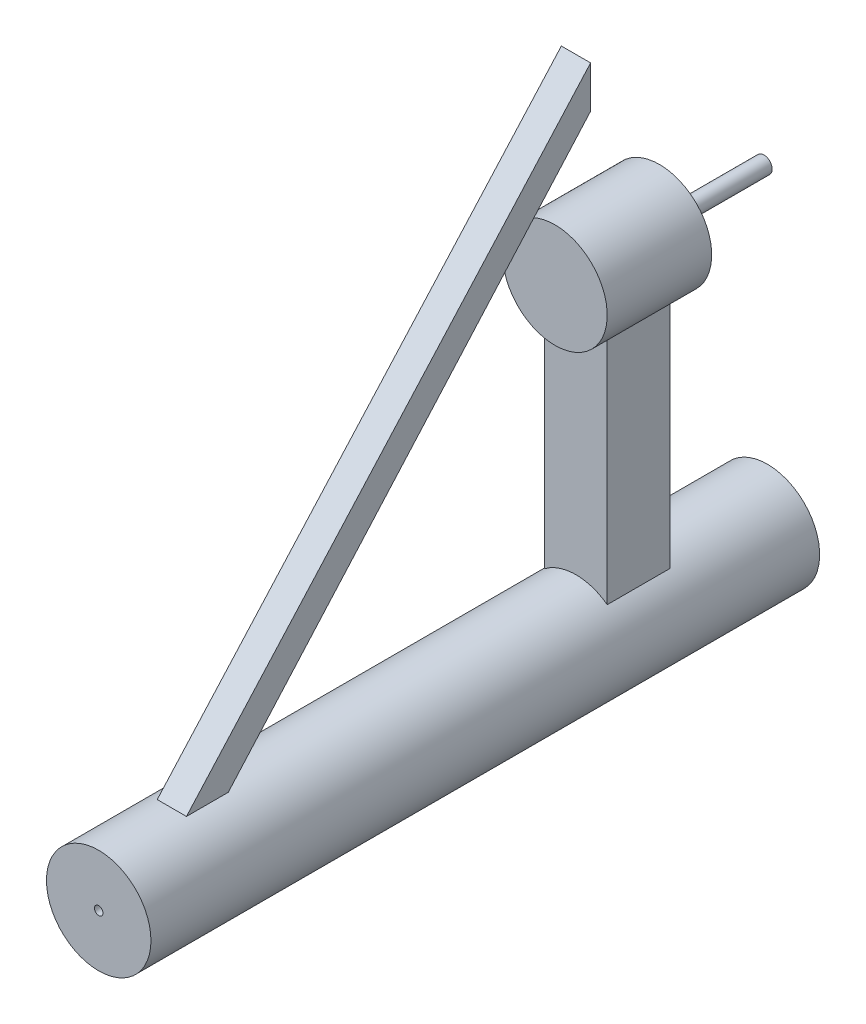
SolidWorks part; units mm, degrees
ref_plane "Alzado" through (0, 0, 0) normal (0, 0, 1) x (1, 0, 0)
ref_plane "Planta" through (0, 0, 0) normal (0, 1, 0) x (1, 0, 0)
ref_plane "Vista lateral" through (0, 0, 0) normal (1, 0, 0) x (0, 0, -1)
sketch "Croquis1" plane through (0, 0, 0) normal (0, 0, 1) x (1, 0, 0)
  circle A0 centre (0, 0) radius 25
  dimension "D1" = 50
extrude "Saliente-Extruir1" add sketch "Croquis1" along normal blind 270
sketch "Croquis2" plane through (0, 0, 0) normal (0, 1, 0) x (1, 0, 0)
  line L3 (-15.05, -11.6046) -> (14.95, -11.6046)
  line L4 (-15.05, -11.6046) -> (-15.05, -41.6046)
  line L5 (-15.05, -41.6046) -> (14.95, -41.6046)
  line L6 (14.95, -11.6046) -> (14.95, -41.6046)
  line L7 (-15.05, -11.6046) -> (14.95, -41.6046) construction
  line L8 (-15.05, -41.6046) -> (14.95, -11.6046) construction
  dimension "D1" = 30
  dimension "D3" = 30
extrude "Saliente-Extruir13" add sketch "Croquis2" along normal blind 150
ref_plane "Plano5" through (0, 0, 11.6046) normal (0, 0, -1) x (-1, 0, 0)
sketch "Croquis14" plane through (0, 0, 11.6046) normal (0, 0, -1) x (-1, 0, 0)
  line L0 (-14.95, 150) -> (15.05, 150) construction
  circle A0 centre (0.05, 150) radius 25
  dimension "D1" = 50
extrude "Saliente-Extruir14" add sketch "Croquis14" along normal blind 10 and the other way blind 40
ref_plane "Plano6" through (0, 0, 1.6046) normal (0, 0, -1) x (-1, 0, 0)
sketch "Croquis15" plane through (0, 0, 0) normal (1, 0, 0) x (0, 0, -1)
  line L0 (-41.6046, 240.6046) -> (-235, 25)
  line L2 (-41.6046, 25) -> (-270, 25) construction
  line L4 (-41.6046, 130) -> (-41.6046, 20.0374) construction
  line L5 (-235, 25) -> (-215, 25)
  line L6 (-41.6046, 240.6046) -> (-41.6046, 220.6046)
  line L7 (-41.6046, 220.6046) -> (-215, 25)
  dimension "D3" = 20
  dimension "D4" = 20
extrude "Saliente-Extruir15" add sketch "Croquis15" along normal blind 7 and the other way blind 7 separate body
ref_plane "Plano9" through (0, 0, 0) normal (0, 0, -1) x (-1, 0, 0)
sketch "Croquis17" plane through (0, 0, 0) normal (0, 0, -1) x (-1, 0, 0)
  circle A0 centre (0, 0) radius 25
  dimension "D1" = 50
extrude "Saliente-Extruir16" add sketch "Croquis17" along normal blind 50
ref_plane "Plano10" through (0, 0, -50) normal (0, 0, -1) x (-1, 0, 0)
ref_plane "Plano11" through (0, 0, 1.6046) normal (0, 0, -1) x (-1, 0, 0)
sketch "Croquis19" plane through (0, 0, 1.6046) normal (0, 0, -1) x (-1, 0, 0)
  circle A0 centre (0.05, 150) radius 3.95
  dimension "D1" = 7.9
extrude "Saliente-Extruir17" add sketch "Croquis19" along normal blind 50
sketch "Croquis20" plane through (0, 0, -50) normal (0, 0, -1) x (-1, 0, 0)
  circle A0 centre (0, 0) radius 3.95
  dimension "D1" = 7.9
extrude "Saliente-Extruir18" add sketch "Croquis20" along normal blind 6
ref_plane "Plano12" through (0, 0, 270) normal (0, 0, 1) x (1, 0, 0)
sketch "Croquis21" plane through (0, 0, 270) normal (0, 0, 1) x (1, 0, 0)
  circle A0 centre (0, 0) radius 2.05
  dimension "D1" = 4.1
extrude "Cortar-Extruir2" cut sketch "Croquis21" against normal blind 10
ref_plane "Plano13" through (0, -25, 0) normal (0, -1, 0) x (-1, 0, 0)
sketch "Croquis22" plane through (0, -25, 0) normal (0, -1, 0) x (-1, 0, 0)
  line L6 (-10, 14.1977) -> (10, 14.1977)
  line L7 (-10, 14.1977) -> (-10, 34.1977)
  line L8 (-10, 34.1977) -> (10, 34.1977)
  line L9 (10, 14.1977) -> (10, 34.1977)
  dimension "D1" = 20
  dimension "D2" = 20
extrude "Cortar-Extruir3" cut sketch "Croquis22" against normal blind 20
sketch "Croquis23" plane through (0, 0, 0) normal (1, 0, 0) x (0, 0, -1)
  line L0 (-51.6046, 125) -> (-51.6046, -71.0891) construction
  line L1 (-51.6046, 175) -> (-51.6046, 125) construction
  line L2 (-270, 0) -> (-51.6046, 0) construction
  line L3 (-270, 27.5) -> (-270, -27.5) construction
  dimension "D1" = 218.3954
sketch "Croquis25" plane through (0, 0, -50) normal (0, 0, -1) x (-1, 0, 0)
  line L0 (0, 0) -> (0, 179) construction
  dimension "D1" = 179
